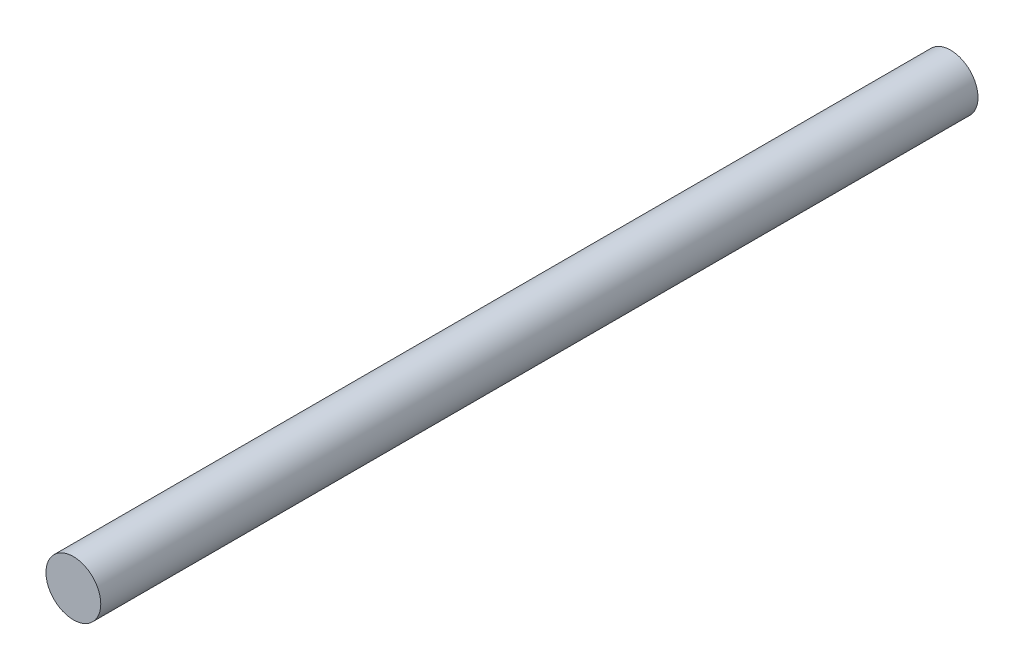
SolidWorks part; units mm, degrees
ref_plane "Front Plane" through (0, 0, 0) normal (0, 0, 1) x (1, 0, 0)
ref_plane "Top Plane" through (0, 0, 0) normal (0, 1, 0) x (1, 0, 0)
ref_plane "Right Plane" through (0, 0, 0) normal (1, 0, 0) x (0, 0, -1)
sketch "Sketch1" plane through (0, 0, 0) normal (0, 0, 1) x (1, 0, 0)
  circle A0 centre (0, 0) radius 12.7
  dimension "D1" = 25.4
extrude "Boss-Extrude1" add sketch "Sketch1" along normal blind 406.4
scale "Scale1" scale about centroid uniform scaling yes scale factor 0.5
